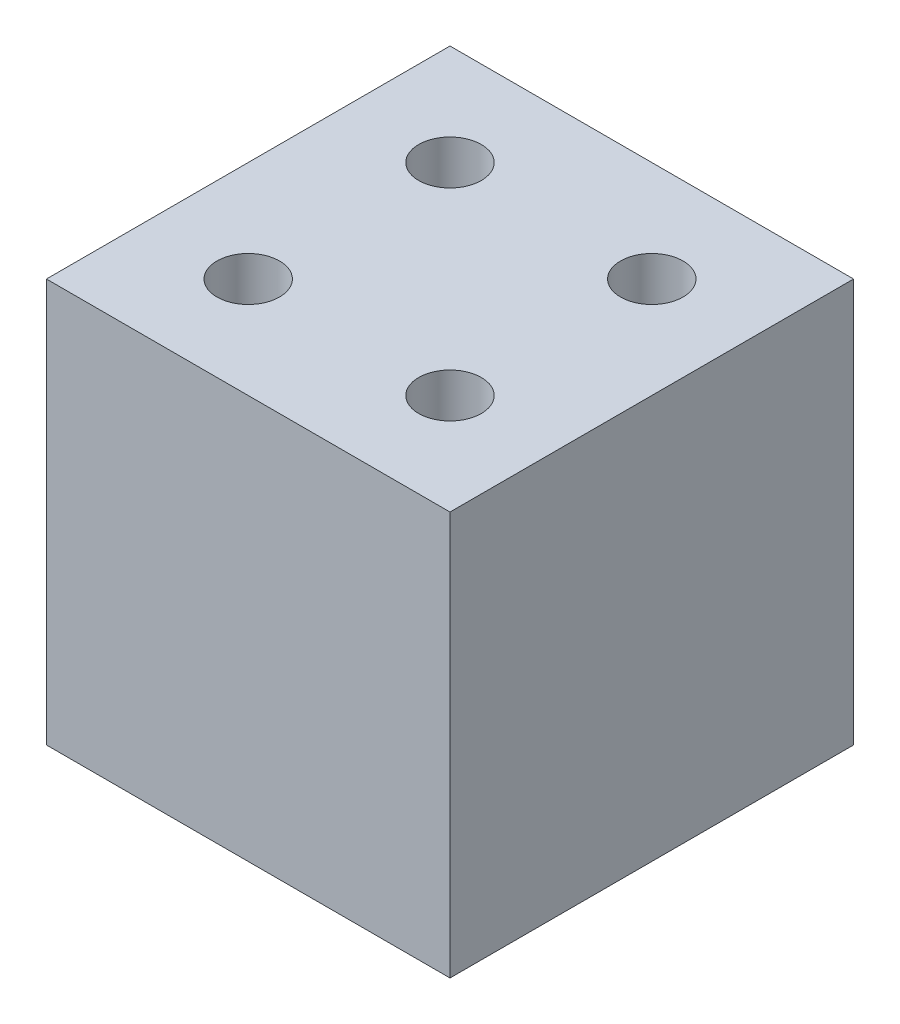
SolidWorks part; units mm, degrees
ref_plane "前视基准面" through (0, 0, 0) normal (0, 0, 1) x (1, 0, 0)
ref_plane "上视基准面" through (0, 0, 0) normal (0, 1, 0) x (1, 0, 0)
ref_plane "右视基准面" through (0, 0, 0) normal (1, 0, 0) x (0, 0, -1)
sketch "草图1" plane through (0, 0, 0) normal (0, 1, 0) x (1, 0, 0)
  line L1 (-5, -5) -> (5, -5) construction
  line L2 (-5, -5) -> (-5, 5) construction
  line L3 (-5, 5) -> (5, 5) construction
  line L4 (5, -5) -> (5, 5) construction
  line L5 (-5, -5) -> (5, 5) construction
  line L6 (-5, 5) -> (5, -5) construction
  line L7 (-10, -10) -> (10, -10)
  line L8 (-10, -10) -> (-10, 10)
  line L9 (-10, 10) -> (10, 10)
  line L10 (10, -10) -> (10, 10)
  line L11 (-10, -10) -> (10, 10) construction
  line L12 (-10, 10) -> (10, -10) construction
  circle A0 centre (-5, 5) radius 1.55
  circle A1 centre (5, 5) radius 1.55
  circle A2 centre (-5, -5) radius 1.55
  circle A3 centre (5, -5) radius 1.55
  point P0 (0, 0)
  point P6 (0, 0)
  dimension "D1" = 3.1
  dimension "D2" = 10
  dimension "D3" = 10
  dimension "D4" = 20
  dimension "D5" = 20
extrude "凸台-拉伸1" add sketch "草图1" along normal blind 20
